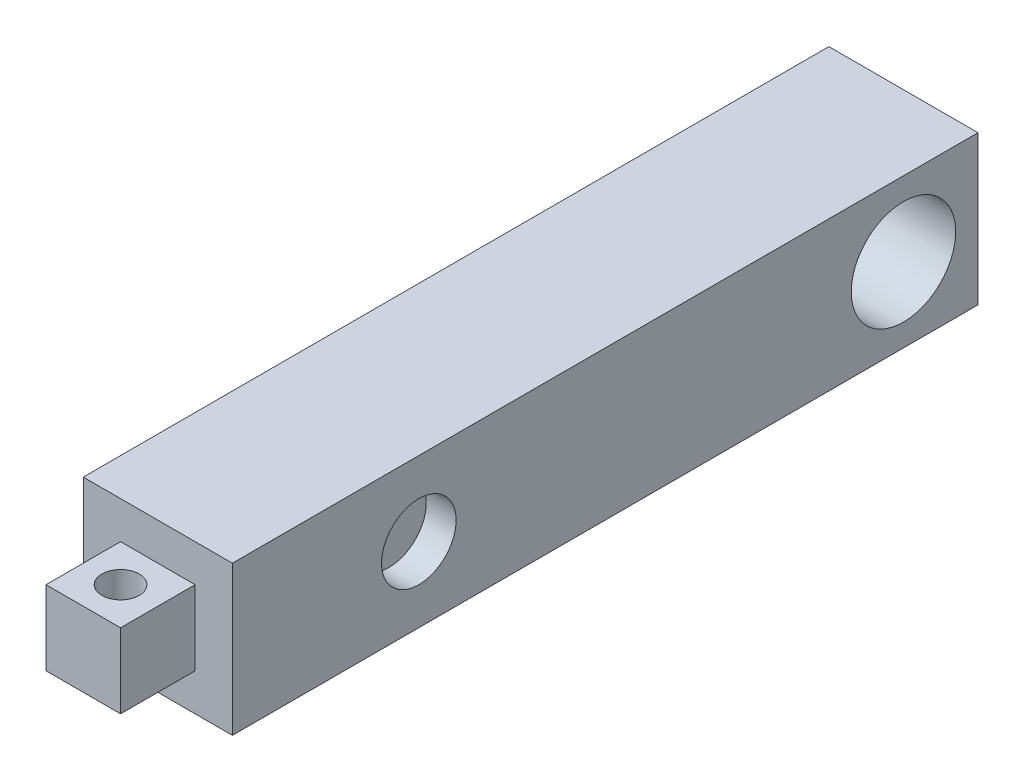
SolidWorks part; units mm, degrees
ref_plane "Front Plane" through (0, 0, 0) normal (0, 0, 1) x (1, 0, 0)
ref_plane "Top Plane" through (0, 0, 0) normal (0, 1, 0) x (1, 0, 0)
ref_plane "Right Plane" through (0, 0, 0) normal (1, 0, 0) x (0, 0, -1)
sketch "Sketch1" plane through (0, 0, 0) normal (0, 0, 1) x (1, 0, 0)
  line L1 (-100, -100) -> (100, -100)
  line L2 (-100, -100) -> (-100, 100)
  line L3 (-100, 100) -> (100, 100)
  line L4 (100, -100) -> (100, 100)
  line L5 (-100, -100) -> (100, 100) construction
  line L6 (-100, 100) -> (100, -100) construction
  point P0 (0, 0)
extrude "Boss-Extrude1" add sketch "Sketch1" along normal blind 1000
sketch "Sketch2" plane through (100, 0, 0) normal (1, 0, 0) x (0, 0, -1)
  line L0 (0, 0) -> (-100, 0) construction
  circle A0 centre (-100, 0) radius 70
extrude "Cut-Extrude1" cut sketch "Sketch2" against normal blind 300 and the other way blind 100
sketch "Sketch3" plane through (0, 0, 1000) normal (0, 0, 1) x (1, 0, 0)
  line L1 (50, 50) -> (-50, 50)
  line L2 (50, 50) -> (50, -50)
  line L3 (50, -50) -> (-50, -50)
  line L4 (-50, 50) -> (-50, -50)
  line L5 (50, 50) -> (-50, -50) construction
  line L6 (50, -50) -> (-50, 50) construction
  point P0 (0, 0)
extrude "Boss-Extrude2" add sketch "Sketch3" along normal blind 100
sketch "Sketch4" plane through (0, -50, 0) normal (0, -1, 0) x (-1, 0, 0)
  line L0 (-50, -1100) -> (50, -1000) construction
  line L1 (-50, -1000) -> (50, -1100) construction
  circle A0 centre (0, -1050) radius 25
extrude "Cut-Extrude2" cut sketch "Sketch4" against normal blind 130 and the other way blind 20
sketch "Sketch5" plane through (-100, 0, 0) normal (-1, 0, 0) x (0, 0, 1)
  line L0 (1000, 0) -> (750, 0) construction
  line L1 (1000, 50) -> (1000, -50) construction
sketch "Sketch6" plane through (100, 0, 0) normal (1, 0, 0) x (0, 0, -1)
  line L0 (-1000, 0) -> (-750, 0) construction
  line L1 (-1000, -100) -> (-1000, 100) construction
  circle A1 centre (-750, 0) radius 50
sketch "Sketch7" plane through (-100, 0, 0) normal (-1, 0, 0) x (0, 0, 1)
  circle A0 centre (750, 0) radius 50
extrude "Cut-Extrude5" cut sketch "Sketch7" against normal blind 40 contours A0
extrude "Cut-Extrude6" cut sketch "Sketch6" against normal blind 40
